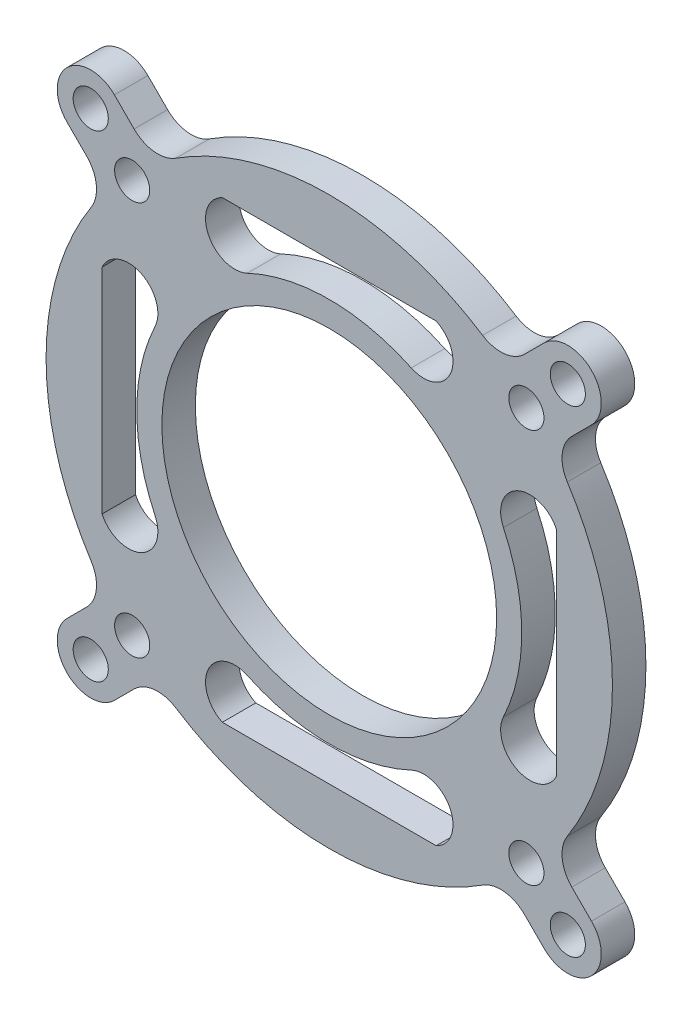
SolidWorks part; units mm, degrees
ref_plane "前视基准面" through (0, 0, 0) normal (0, 0, 1) x (1, 0, 0)
ref_plane "上视基准面" through (0, 0, 0) normal (0, 1, 0) x (1, 0, 0)
ref_plane "右视基准面" through (0, 0, 0) normal (1, 0, 0) x (0, 0, -1)
sketch "草图1" plane through (0, 0, 0) normal (0, 0, 1) x (1, 0, 0)
  line L0 (0, 0) -> (47.1, 0) construction
  line L1 (0, 0) -> (0, -47.1) construction
  line L2 (0, 0) -> (47.1, -47.1) construction
  line L3 (47.1, -47.1) -> (52.0497, -52.0497) construction
  line L6 (54.05, 6.95) -> (-6.95, 6.95) construction
  line L8 (23.55, -23.55) -> (23.55, -16.6688) construction
  line L9 (54.05, 6.95) -> (-6.95, -54.05) construction
  line L14 (52.0497, -52.0497) -> (48.0497, -56.0497) construction
  line L23 (-1.2931, 6.95) -> (48.3931, 6.95) construction
  line L27 (49.2213, -54.8782) -> (46.8701, -52.5269)
  line L28 (54.8782, -49.2213) -> (52.5269, -46.8701)
  line L29 (-2.1213, -54.8782) -> (0.2299, -52.5269)
  line L47 (-7.7782, -49.2213) -> (-5.4269, -46.8701)
  line L48 (-7.7782, 2.1213) -> (-5.4269, -0.2299)
  line L49 (23.55, -23.55) -> (41.8752, 4.8928) construction
  line L50 (10.775, 3.594) -> (36.325, 3.594)
  line L51 (-3.594, -36.325) -> (-3.594, -10.775)
  line L52 (10.775, -50.694) -> (36.325, -50.694)
  line L53 (-2.1213, 7.7782) -> (0.2299, 5.4269)
  line L54 (50.694, -10.775) -> (50.694, -36.325)
  line L60 (49.2213, 7.7782) -> (46.8701, 5.4269)
  line L61 (54.8782, 2.1213) -> (52.5269, -0.2299)
  circle A3 centre (47.1, -47.1) radius 2.1
  circle A4 centre (23.55, -23.55) radius 20
  circle A15 centre (52.0497, -52.0497) radius 2.1
  circle A16 centre (52.0497, -52.0497) radius 4 construction
  arc A17 (49.2213, -54.8782) -> (54.8782, -49.2213) centre (52.0497, -52.0497) ccw
  arc A18 (-7.7782, -49.2213) -> (-2.1213, -54.8782) centre (-4.9497, -52.0497) ccw
  arc A19 (-2.1213, 7.7782) -> (-7.7782, 2.1213) centre (-4.9497, 4.9497) ccw
  arc A20 (54.8782, 2.1213) -> (49.2213, 7.7782) centre (52.0497, 4.9497) ccw
  circle A25 centre (-4.9497, -52.0497) radius 2.1
  circle A26 centre (-4.9497, 4.9497) radius 2.1
  circle A27 centre (52.0497, 4.9497) radius 2.1
  circle A28 centre (0, -47.1) radius 2.1
  circle A29 centre (0, 0) radius 2.1
  circle A30 centre (47.1, 0) radius 2.1
  circle A31 centre (23.55, -23.55) radius 33.835 construction
  arc A32 (5.2248, -51.9928) -> (41.8752, -51.9928) centre (23.55, -23.55) ccw
  arc A33 (51.9928, -41.8752) -> (51.9928, -5.2248) centre (23.55, -23.55) ccw
  arc A34 (5.2248, 4.8928) -> (41.8752, 4.8928) centre (23.55, -23.55) cw
  arc A35 (-4.8928, -5.2248) -> (-4.8928, -41.8752) centre (23.55, -23.55) ccw
  arc A36 (-4.8928, -5.2248) -> (-5.4269, -0.2299) centre (-8.2553, -3.0584) ccw
  arc A37 (0.2299, 5.4269) -> (5.2248, 4.8928) centre (3.0584, 8.2553) ccw
  arc A38 (41.8752, 4.8928) -> (46.8701, 5.4269) centre (44.0416, 8.2553) ccw
  arc A39 (52.5269, -0.2299) -> (51.9928, -5.2248) centre (55.3553, -3.0584) ccw
  arc A40 (51.9928, -41.8752) -> (52.5269, -46.8701) centre (55.3553, -44.0416) ccw
  arc A41 (46.8701, -52.5269) -> (41.8752, -51.9928) centre (44.0416, -55.3553) ccw
  arc A42 (5.2248, -51.9928) -> (0.2299, -52.5269) centre (3.0584, -55.3553) ccw
  arc A43 (-5.4269, -46.8701) -> (-4.8928, -41.8752) centre (-8.2553, -44.0416) ccw
  circle A44 centre (23.55, -23.55) radius 23 construction
  circle A45 centre (23.55, -23.55) radius 30 construction
  circle A48 centre (34.8346, 0.4272) radius 3.5 construction
  circle A49 centre (12.2654, 0.4272) radius 3.5 construction
  arc A51 (33.3442, -2.7396) -> (13.7558, -2.7396) centre (23.55, -23.55) ccw
  arc A52 (36.325, 3.594) -> (33.3442, -2.7396) centre (34.8346, 0.4272) cw
  arc A53 (13.7558, -2.7396) -> (10.775, 3.594) centre (12.2654, 0.4272) cw
  arc A54 (44.3604, -13.7558) -> (50.694, -10.775) centre (47.5272, -12.2654) cw
  arc A55 (50.694, -36.325) -> (44.3604, -33.3442) centre (47.5272, -34.8346) cw
  arc A57 (44.3604, -33.3442) -> (44.3604, -13.7558) centre (23.55, -23.55) ccw
  arc A58 (33.3442, -44.3604) -> (36.325, -50.694) centre (34.8346, -47.5272) cw
  arc A59 (10.775, -50.694) -> (13.7558, -44.3604) centre (12.2654, -47.5272) cw
  arc A61 (13.7558, -44.3604) -> (33.3442, -44.3604) centre (23.55, -23.55) ccw
  arc A62 (2.7396, -33.3442) -> (-3.594, -36.325) centre (-0.4272, -34.8346) cw
  arc A63 (-3.594, -10.775) -> (2.7396, -13.7558) centre (-0.4272, -12.2654) cw
  arc A65 (2.7396, -13.7558) -> (2.7396, -33.3442) centre (23.55, -23.55) ccw
  point P67 (50.1356, -44.4788)
  point P70 (44.4788, -50.1356)
  dimension "D2" = 4
  dimension "D3" = 4
  dimension "D8" = 4
  dimension "D10" = 4
  dimension "D5" = 4
  dimension "D1" = 47.1
  dimension "D11" = 4
extrude "凸台-拉伸1" add sketch "草图1" along normal blind 4
